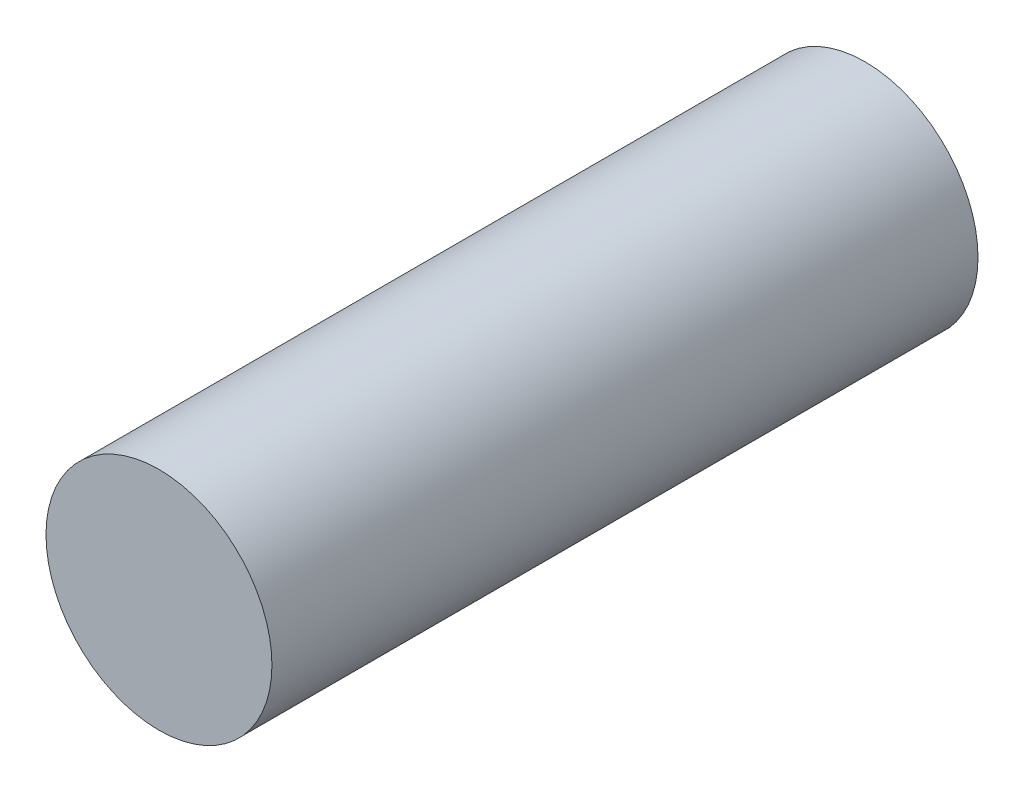
SolidWorks part; units mm, degrees
ref_plane "前视基准面" through (0, 0, 0) normal (0, 0, 1) x (1, 0, 0)
ref_plane "上视基准面" through (0, 0, 0) normal (0, 1, 0) x (1, 0, 0)
ref_plane "右视基准面" through (0, 0, 0) normal (1, 0, 0) x (0, 0, -1)
sketch "草图1" plane through (0, 0, 0) normal (0, 0, 1) x (1, 0, 0)
  circle A0 centre (0, 0) radius 4
extrude "凸台-拉伸1" add sketch "草图1" along normal blind 25 contours A0
